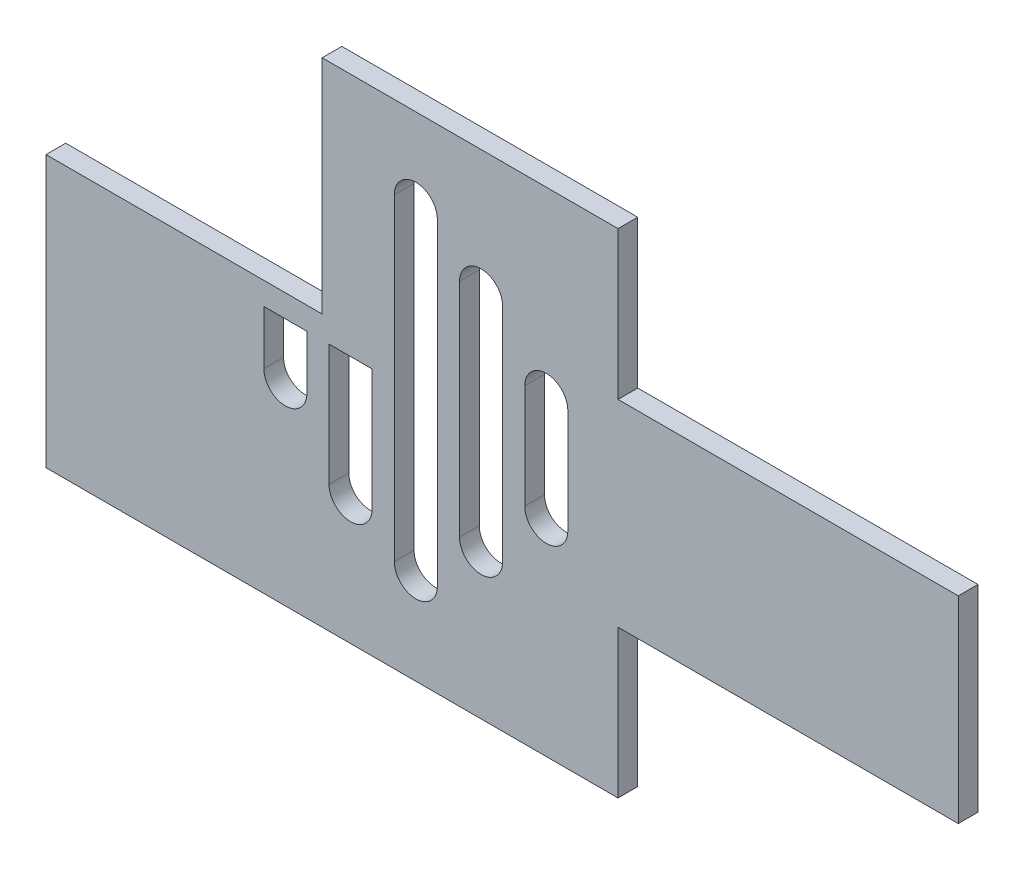
SolidWorks part; units mm, degrees
ref_plane "Front Plane" through (0, 0, 0) normal (0, 0, 1) x (1, 0, 0)
ref_plane "Top Plane" through (0, 0, 0) normal (0, 1, 0) x (1, 0, 0)
ref_plane "Right Plane" through (0, 0, 0) normal (1, 0, 0) x (0, 0, -1)
sketch "Sketch1" plane through (0, 0, 0) normal (0, 0, 1) x (1, 0, 0)
  line L0 (0, 33.2683) -> (0, -31.1612) construction
  line L1 (-75, -50) -> (75, -50) construction
  line L3 (-75, 50) -> (75, 50) construction
  line L5 (-75, -50) -> (75, 50) construction
  line L6 (-75, 50) -> (75, -50) construction
  line L7 (4.3648, 33.2683) -> (4.3648, -31.1612)
  line L8 (-4.3648, 33.2683) -> (-4.3648, -31.1612)
  line L9 (-13.2297, 29.6339) -> (-13.2297, -24.2226) construction
  line L10 (-8.8648, 29.6339) -> (-8.8648, -24.2226) construction
  line L11 (-17.5945, 29.6339) -> (-17.5945, -24.2226) construction
  line L12 (13.2297, 24.6777) -> (13.2297, -20.2577) construction
  line L13 (17.5945, 24.6777) -> (17.5945, -20.2577)
  line L14 (8.8648, 24.6777) -> (8.8648, -20.2577)
  line L15 (-26.4594, 15.7567) -> (-26.4594, -10.5107) construction
  line L16 (-22.0945, 15.7567) -> (-22.0945, -10.5107) construction
  line L17 (-30.8242, 15.7567) -> (-30.8242, -10.5107) construction
  line L18 (26.4594, 12.9483) -> (26.4594, -8.1978) construction
  line L19 (30.8242, 12.9483) -> (30.8242, -8.1978)
  line L20 (22.0945, 12.9483) -> (22.0945, -8.1978)
  line L21 (0, 80.4433) -> (0, -75.6846) construction
  line L22 (56, 35) -> (60, 35) construction
  line L23 (56, 35) -> (56, 20) construction
  line L24 (56, 20) -> (60, 20) construction
  line L25 (60, 35) -> (60, 20) construction
  line L26 (-110.7456, 0) -> (128.9906, 0) construction
  line L27 (56, -20) -> (60, -20) construction
  line L28 (56, -35) -> (56, -20) construction
  line L29 (60, -35) -> (60, -20) construction
  line L30 (56, -35) -> (60, -35) construction
  line L35 (-56, 20) -> (-60, 20) construction
  line L36 (-56, 35) -> (-56, 20) construction
  line L37 (-60, 35) -> (-60, 20) construction
  line L38 (-56, 35) -> (-60, 35) construction
  line L42 (75, 50) -> (110, 50) construction
  line L51 (110, 50) -> (110, -50) construction
  line L52 (110, -50) -> (75, -50) construction
  line L53 (-75, 50) -> (-75, -50) construction
  line L54 (105, 35) -> (101, 35) construction
  line L55 (105, 35) -> (105, 20) construction
  line L56 (105, 20) -> (101, 20) construction
  line L57 (101, 35) -> (101, 20) construction
  line L59 (105, -20) -> (105, -35) construction
  line L60 (105, -35) -> (101, -35) construction
  line L61 (101, -20) -> (101, -35) construction
  line L62 (-19, 50) -> (-19, 5)
  line L63 (-19, 5) -> (-75, 5)
  line L64 (-19, 50) -> (75, 50) construction
  line L65 (-75, 5) -> (-75, -50)
  line L66 (41, 50) -> (41, 20)
  line L67 (41, 20) -> (110, 20)
  line L68 (110, 20) -> (110, -20)
  line L69 (110, -20) -> (41, -20)
  line L70 (41, -20) -> (41, -50)
  line L71 (41, 50) -> (-19, 50)
  line L72 (41, -50) -> (-75, -50)
  line L73 (101, -20) -> (105, -20) construction
  line L74 (-30.8242, 0.4161) -> (-22.0945, 0.4161)
  line L75 (-30.8242, 0.4161) -> (-30.8242, -10.5107)
  line L76 (-22.0945, -10.5107) -> (-22.0945, 0.4161)
  line L77 (-17.5945, 0.4161) -> (-8.8648, 0.4161)
  line L78 (-8.8648, 0.4161) -> (-8.8648, -24.2226)
  line L79 (-17.5945, -24.2226) -> (-17.5945, 0.4161)
  arc A1 (4.3648, 33.2683) -> (-4.3648, 33.2683) centre (0, 33.2683) ccw
  arc A2 (-4.3648, -31.1612) -> (4.3648, -31.1612) centre (0, -31.1612) ccw
  arc A3 (-8.8648, 29.6339) -> (-17.5945, 29.6339) centre (-13.2297, 29.6339) ccw construction
  arc A4 (-17.5945, -24.2226) -> (-8.8648, -24.2226) centre (-13.2297, -24.2226) ccw construction
  arc A5 (17.5945, 24.6777) -> (8.8648, 24.6777) centre (13.2297, 24.6777) ccw
  arc A6 (8.8648, -20.2577) -> (17.5945, -20.2577) centre (13.2297, -20.2577) ccw
  arc A7 (-22.0945, 15.7567) -> (-30.8242, 15.7567) centre (-26.4594, 15.7567) ccw construction
  arc A8 (-30.8242, -10.5107) -> (-22.0945, -10.5107) centre (-26.4594, -10.5107) ccw construction
  arc A9 (30.8242, 12.9483) -> (22.0945, 12.9483) centre (26.4594, 12.9483) ccw
  arc A10 (22.0945, -8.1978) -> (30.8242, -8.1978) centre (26.4594, -8.1978) ccw
  arc A11 (-30.8242, -10.5107) -> (-22.0945, -10.5107) centre (-26.4594, -10.5107) ccw
  arc A12 (-17.5945, -24.2226) -> (-8.8648, -24.2226) centre (-13.2297, -24.2226) ccw
  point P0 (0, 0)
  point P8 (0, 1.0536)
  point P13 (-13.2297, 2.7056)
  point P20 (13.2297, 2.21)
  point P27 (-26.4594, 2.623)
  point P34 (26.4594, 2.3752)
  dimension "D3" = 4.3648
  dimension "D4" = 4.3648
  dimension "D5" = 4.3648
  dimension "D6" = 4.3648
  dimension "D7" = 4.3648
  dimension "D1" = 100
  dimension "D2" = 150
  dimension "D8" = 4.5
  dimension "D9" = 4.5
  dimension "D10" = 4.5
  dimension "D11" = 4.5
  dimension "D12" = 4
  dimension "D13" = 15
  dimension "D14" = 35
  dimension "D15" = 15
  dimension "D16" = 15
  dimension "D17" = 5
  dimension "D18" = 5
  dimension "D19" = 37
  dimension "D20" = 0
  dimension "D21" = 15
  dimension "D22" = 0
extrude "Boss-Extrude1" add sketch "Sketch1" along normal blind 4
